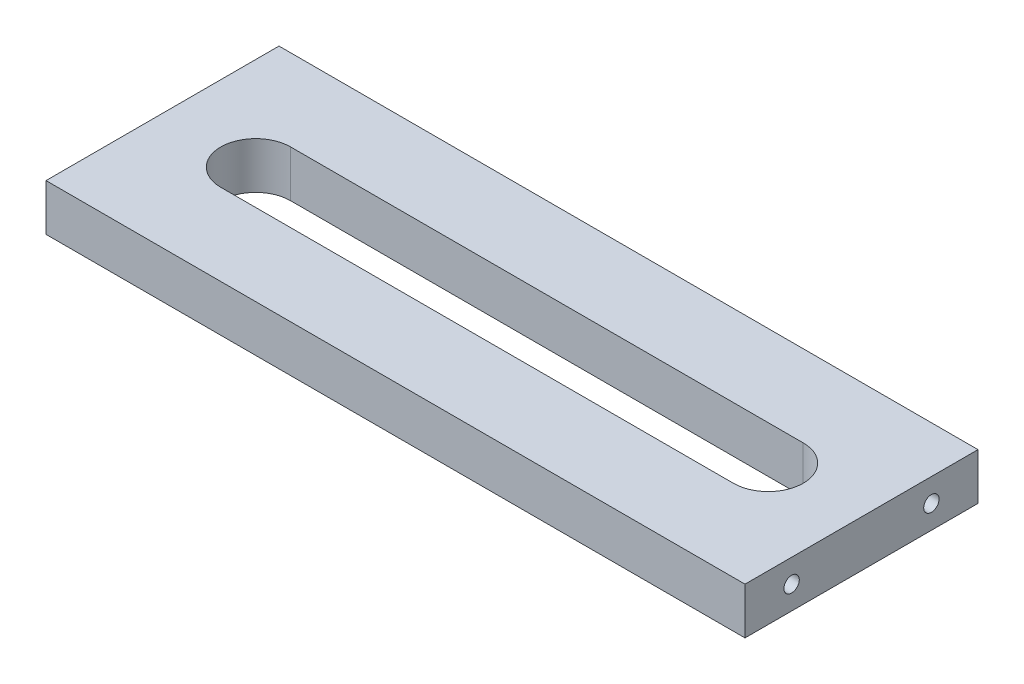
SolidWorks part; units mm, degrees
ref_plane "前视基准面" through (0, 0, 0) normal (0, 0, 1) x (1, 0, 0)
ref_plane "上视基准面" through (0, 0, 0) normal (0, 1, 0) x (1, 0, 0)
ref_plane "右视基准面" through (0, 0, 0) normal (1, 0, 0) x (0, 0, -1)
sketch "草图1" plane through (0, 0, 0) normal (0, 1, 0) x (1, 0, 0)
  line L1 (-75, -25) -> (75, -25)
  line L2 (-75, -25) -> (-75, 25)
  line L3 (-75, 25) -> (75, 25)
  line L4 (75, -25) -> (75, 25)
  line L5 (-75, -25) -> (75, 25) construction
  line L6 (-75, 25) -> (75, -25) construction
  point P0 (0, 0)
  dimension "D1" = 150
  dimension "D2" = 50
extrude "凸台-拉伸1" add sketch "草图1" along normal blind 10
sketch "草图2" plane through (0, 10, 0) normal (0, 1, 0) x (1, 0, 0)
  line L0 (-75, 25) -> (-75, -25) construction
  line L1 (75, -25) -> (75, 25) construction
  line L2 (-55, 7.5) -> (55, 7.5)
  line L3 (-55, -7.5) -> (55, -7.5)
  arc A0 (-55, 7.5) -> (-55, -7.5) centre (-55, 0) ccw
  arc A1 (55, -7.5) -> (55, 7.5) centre (55, 0) ccw
  dimension "D3" = 15
  dimension "D4" = 15
  dimension "D1" = 20
  dimension "D2" = 20
extrude "切除-拉伸1" cut sketch "草图2" against normal blind 10
hole_wizard "M4 螺纹孔的螺纹孔钻头1" positions "3D草图2" profile "草图4" hole size "M4" standard "GB"
sketch3d "3D草图2"
  line L0 (-75, 10, -25) -> (-75, 0, -25) construction
  line L1 (-75, 10, -25) -> (-75, 10, 25) construction
  line L2 (-75, 10, 25) -> (-75, 0, 25) construction
  point P0 (-75, 5, -15)
  point P2 (-75, 5, 15)
  dimension "D1" = 10
  dimension "D2" = 5
  dimension "D3" = 10
  dimension "D4" = 5
sketch "草图4" plane through (-75, 5, -15) normal (0, 1, 0) x (0, 0, 1)
  line L0 (0, 0) -> (0, 7.9914)
  line L1 (0, 7.9914) -> (1.65, 7)
  line L2 (1.65, 7) -> (1.65, 0)
  line L5 (1.65, 0) -> (0, 0)
  line L10 (0, 7.9914) -> (-1.65, 7) construction
  line L11 (0, -6.35) -> (0, 107.95) construction
  dimension "孔直径" = 3.3
  dimension "孔深度" = 7
  dimension "导头角度" = 118
hole_wizard "M4 螺纹孔的螺纹孔钻头2" positions "3D草图3" profile "草图5" hole size "M4" standard "GB"
sketch3d "3D草图3"
  line L0 (75, 10, 25) -> (75, 0, 25) construction
  line L1 (75, 10, 25) -> (75, 10, -25) construction
  line L2 (75, 10, -25) -> (75, 0, -25) construction
  point P0 (75, 5, 15)
  point P2 (75, 5, -15)
  point P4 (0, 37.6986, 89.9636)
  dimension "D1" = 10
  dimension "D2" = 5
  dimension "D3" = 10
  dimension "D4" = 5
sketch "草图5" plane through (75, 5, 15) normal (0, 1, 0) x (0, 0, -1)
  line L0 (0, 0) -> (0, 7.9914)
  line L1 (0, 7.9914) -> (1.65, 7)
  line L2 (1.65, 7) -> (1.65, 0)
  line L5 (1.65, 0) -> (0, 0)
  line L10 (0, 7.9914) -> (-1.65, 7) construction
  line L11 (0, -6.35) -> (0, 107.95) construction
  dimension "孔直径" = 3.3
  dimension "孔深度" = 7
  dimension "导头角度" = 118
